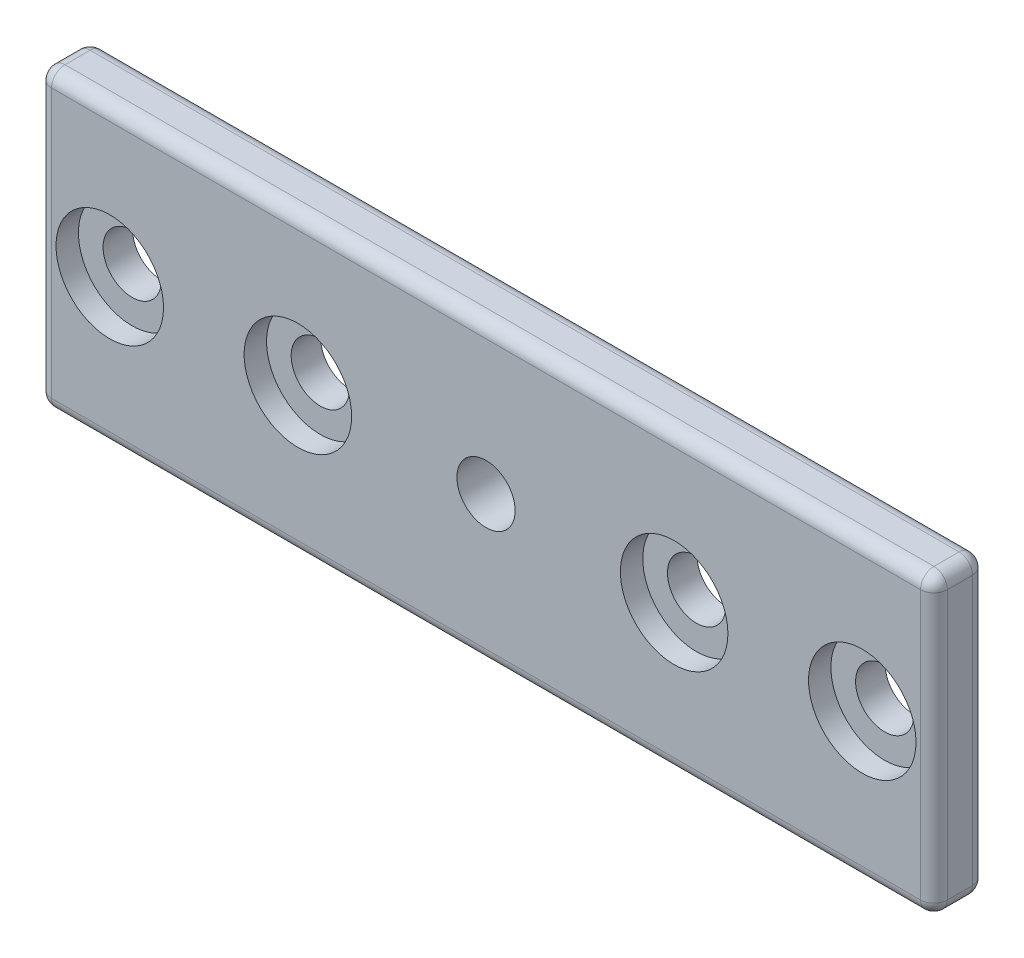
SolidWorks part; units mm, degrees
ref_plane "Front Plane" through (0, 0, 0) normal (0, 0, 1) x (1, 0, 0)
ref_plane "Top Plane" through (0, 0, 0) normal (0, 1, 0) x (1, 0, 0)
ref_plane "Right Plane" through (0, 0, 0) normal (1, 0, 0) x (0, 0, -1)
sketch "Sketch1" plane through (0, 0, 0) normal (0, 0, 1) x (1, 0, 0)
  line L1 (0, 0) -> (100, 0)
  line L2 (0, 0) -> (0, 33)
  line L3 (0, 33) -> (100, 33)
  line L4 (100, 0) -> (100, 33)
  line L5 (0, 0) -> (100, 33) construction
  line L6 (0, 33) -> (100, 0) construction
  point P4 (50, 16.5)
  dimension "D1" = 100
  dimension "D2" = 33
extrude "Boss-Extrude1" add sketch "Sketch1" along normal blind 5.8
sketch "Sketch2" plane through (0, 0, 5.8) normal (0, 0, 1) x (1, 0, 0)
  line L0 (100, 16.5) -> (-4.7879, 16.5) construction
  line L1 (100, 0) -> (100, 33) construction
  line L2 (0, 33) -> (0, 0) construction
  circle A0 centre (8, 16.5) radius 3.25
  circle A1 centre (29, 16.5) radius 3.25
  circle A2 centre (50, 16.5) radius 3.25
  circle A3 centre (71, 16.5) radius 3.25
  circle A4 centre (92, 16.5) radius 3.25
  dimension "D1" = 6.5
  dimension "D2" = 8
  dimension "D3" = 5
extrude "Cut-Extrude1" cut sketch "Sketch2" against normal through all
sketch "Sketch3" plane through (0, 0, 5.8) normal (0, 0, 1) x (1, 0, 0)
  circle A0 centre (8, 16.5) radius 6
  circle A1 centre (29, 16.5) radius 6
  circle A2 centre (71, 16.5) radius 6
  circle A3 centre (92, 16.5) radius 6
  dimension "D1" = 12
  dimension "D2" = 12
  dimension "D3" = 12
  dimension "D4" = 12
extrude "Cut-Extrude5" cut sketch "Sketch3" against normal blind 2.5
fillet "Fillet1" radius 1.5 12 edges at (100, 16.5, 5.8) (100, 16.5, 0) (0, 16.5, 5.8) (0, 16.5, 0) (100, 33, 2.9) (50, 33, 5.8) (0, 33, 2.9) (50, 33, 0) (0, 0, 2.9) (50, 0, 5.8) (100, 0, 2.9) (50, 0, 0)
